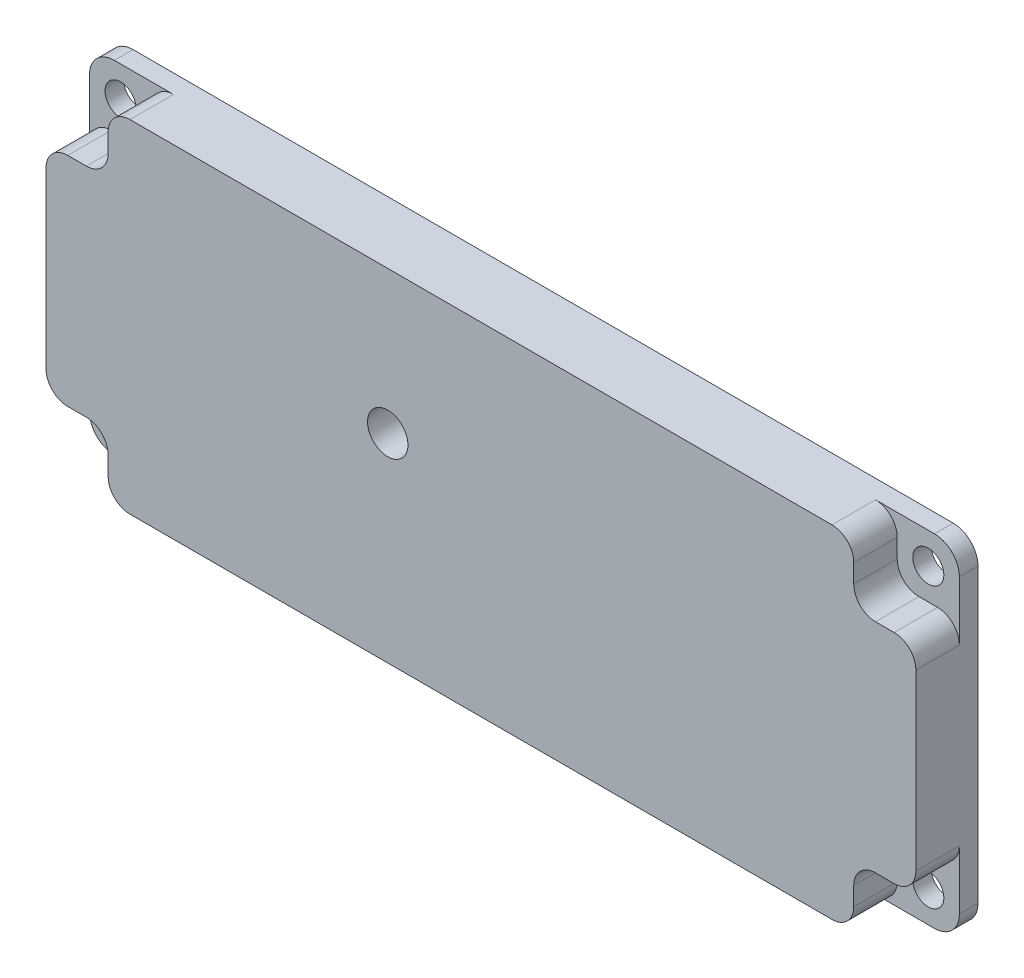
SolidWorks part; units mm, degrees
ref_plane "Front Plane" through (0, 0, 0) normal (0, 0, 1) x (1, 0, 0)
ref_plane "Top Plane" through (0, 0, 0) normal (0, 1, 0) x (1, 0, 0)
ref_plane "Right Plane" through (0, 0, 0) normal (1, 0, 0) x (0, 0, -1)
sketch "Sketch1" plane through (0, 0, 0) normal (0, 0, 1) x (1, 0, 0)
  line L1 (-73.7476, 33.9217) -> (58.2524, 33.9217)
  line L2 (-77.7476, 29.9217) -> (-77.7476, -17.0783)
  line L3 (-73.7476, -21.0783) -> (58.2524, -21.0783)
  line L4 (62.2524, 29.9217) -> (62.2524, -17.0783)
  arc A0 (58.2524, 33.9217) -> (62.2524, 29.9217) centre (58.2524, 29.9217) cw
  arc A1 (62.2524, -17.0783) -> (58.2524, -21.0783) centre (58.2524, -17.0783) cw
  arc A2 (-73.7476, -21.0783) -> (-77.7476, -17.0783) centre (-73.7476, -17.0783) cw
  arc A3 (-77.7476, 29.9217) -> (-73.7476, 33.9217) centre (-73.7476, 29.9217) cw
  circle A4 centre (-22.7476, 10.9217) radius 3.25
  point P6 (62.2524, 33.9217)
  point P11 (-77.7476, -21.0783)
  point P14 (-77.7476, 33.9217)
  dimension "D3" = 4
  dimension "D6" = 6.5
  dimension "D1" = 140
  dimension "D2" = 55
  dimension "D4" = 55
  dimension "D5" = 23
extrude "Boss-Extrude1" add sketch "Sketch1" along normal blind 10
sketch "Sketch2" plane through (0, 0, 10) normal (0, 0, 1) x (1, 0, 0)
  line L0 (-77.7476, 29.9217) -> (-77.7476, -17.0783) construction
  line L1 (-77.7476, 23.9217) -> (-71.2476, 23.9217)
  line L2 (-77.7476, 23.9217) -> (-77.7476, 33.9217)
  line L3 (-77.7476, 33.9217) -> (-67.7476, 33.9217)
  line L4 (-67.7476, 27.4217) -> (-67.7476, 33.9217)
  line L5 (58.2524, 33.9217) -> (-73.7476, 33.9217) construction
  line L6 (-73.7476, -21.0783) -> (58.2524, -21.0783) construction
  line L7 (-77.7476, -11.0783) -> (-71.2476, -11.0783)
  line L8 (-77.7476, -11.0783) -> (-77.7476, -21.0783)
  line L9 (-77.7476, -21.0783) -> (-67.7476, -21.0783)
  line L10 (-67.7476, -14.5783) -> (-67.7476, -21.0783)
  line L11 (62.2524, -17.0783) -> (62.2524, 29.9217) construction
  line L12 (52.2524, -21.0783) -> (62.2524, -21.0783)
  line L13 (52.2524, -21.0783) -> (52.2524, -14.5783)
  line L14 (55.7524, -11.0783) -> (62.2524, -11.0783)
  line L15 (62.2524, -21.0783) -> (62.2524, -11.0783)
  line L17 (62.2524, 23.9217) -> (55.7524, 23.9217)
  line L18 (62.2524, 23.9217) -> (62.2524, 33.9217)
  line L19 (62.2524, 33.9217) -> (52.2524, 33.9217)
  line L20 (52.2524, 27.4217) -> (52.2524, 33.9217)
  arc A0 (-71.2476, -11.0783) -> (-67.7476, -14.5783) centre (-71.2476, -14.5783) cw
  arc A1 (52.2524, -14.5783) -> (55.7524, -11.0783) centre (55.7524, -14.5783) cw
  arc A2 (55.7524, 23.9217) -> (52.2524, 27.4217) centre (55.7524, 27.4217) cw
  arc A3 (-67.7476, 27.4217) -> (-71.2476, 23.9217) centre (-71.2476, 27.4217) cw
  point P26 (-67.7476, -11.0783)
  point P29 (52.2524, -11.0783)
  point P32 (52.2524, 23.9217)
  point P35 (-67.7476, 23.9217)
  dimension "D9" = 3.5
  dimension "D1" = 10
  dimension "D2" = 10
  dimension "D3" = 10
  dimension "D4" = 10
  dimension "D5" = 10
  dimension "D6" = 10
  dimension "D7" = 10
  dimension "D8" = 10
extrude "Cut-Extrude1" cut sketch "Sketch2" against normal blind 7
sketch "Sketch3" plane through (0, 0, 3) normal (0, 0, 1) x (1, 0, 0)
  line L0 (-67.7476, 27.4217) -> (-67.7476, 33.9217) construction
  line L1 (-77.7476, 23.9217) -> (-71.2476, 23.9217) construction
  line L2 (52.2524, 33.9217) -> (52.2524, 27.4217) construction
  line L3 (55.7524, 23.9217) -> (62.2524, 23.9217) construction
  line L4 (62.2524, -11.0783) -> (55.7524, -11.0783) construction
  line L6 (52.2524, -14.5783) -> (52.2524, -21.0783) construction
  line L7 (-67.7476, -21.0783) -> (-67.7476, -14.5783) construction
  line L8 (-71.2476, -11.0783) -> (-77.7476, -11.0783) construction
  circle A0 centre (-72.7476, 28.9217) radius 2.5
  circle A1 centre (57.2524, 28.9217) radius 2.5
  circle A2 centre (57.2524, -16.0783) radius 2.5
  circle A3 centre (-72.7476, -16.0783) radius 2.5
  dimension "D3" = 5
  dimension "D6" = 5
  dimension "D9" = 5
  dimension "D10" = 5
  dimension "D12" = 5
  dimension "D1" = 5
  dimension "D2" = 5
  dimension "D4" = 5
  dimension "D5" = 5
  dimension "D7" = 5
  dimension "D8" = 5
  dimension "D11" = 5
extrude "Cut-Extrude2" cut sketch "Sketch3" against normal blind 10
fillet "Fillet1" radius 3.5 8 edges at (62.2524, 23.9217, 6.5) (52.2524, 33.9217, 6.5) (62.2524, -11.0783, 6.5) (52.2524, -21.0783, 6.5) (-67.7476, 33.9217, 6.5) (-77.7476, 23.9217, 6.5) (-67.7476, -21.0783, 6.5) (-77.7476, -11.0783, 6.5)
